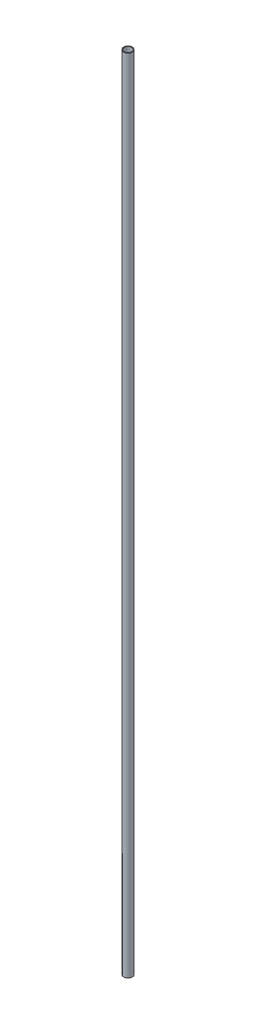
SolidWorks part; units mm, degrees
ref_plane "Front Plane" through (0, 0, 0) normal (0, 0, 1) x (1, 0, 0)
ref_plane "Top Plane" through (0, 0, 0) normal (0, 1, 0) x (1, 0, 0)
ref_plane "Right Plane" through (0, 0, 0) normal (1, 0, 0) x (0, 0, -1)
sketch "Sketch1" plane through (-248.2896, -730.2857, -323.2914) normal (0, 1, 0) x (-0.0333, 0, -0.9994)
  circle A0 centre (96.8068, 114.3442) radius 17.4625
  circle A1 centre (96.8068, 114.3442) radius 14.9225
  dimension "D1" = 34.925
  dimension "D2" = 2.54
extrude "Boss-Extrude1" add sketch "Sketch1" along normal blind 3200.4
